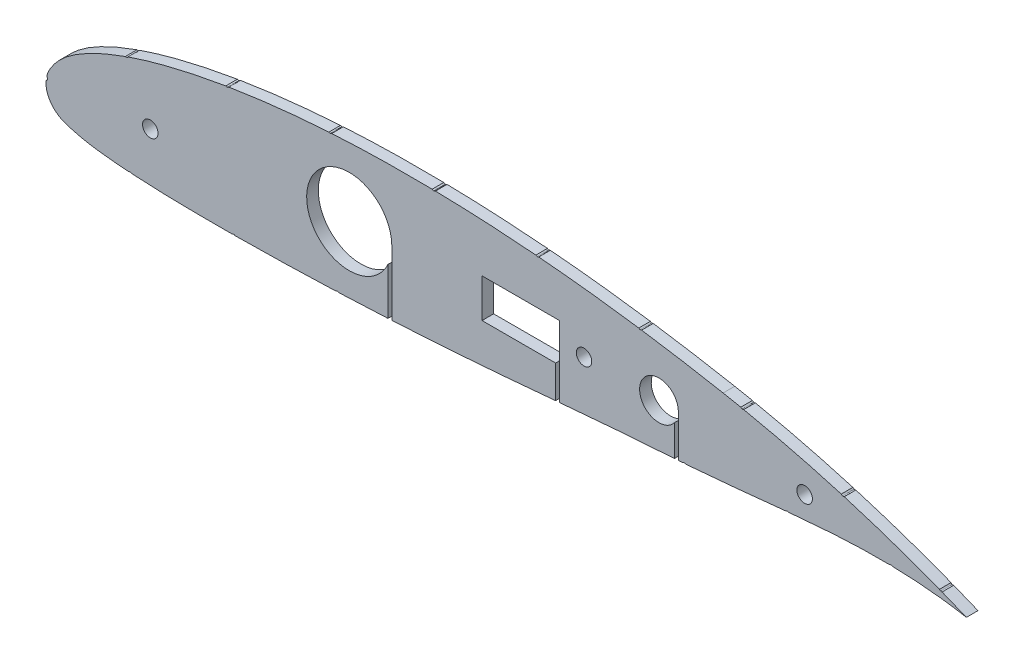
SolidWorks part; units mm, degrees
ref_plane "Front" through (0, 0, 0) normal (0, 0, 1) x (1, 0, 0)
ref_plane "Top" through (0, 0, 0) normal (0, 1, 0) x (1, 0, 0)
ref_plane "Right" through (0, 0, 0) normal (1, 0, 0) x (0, 0, -1)
sketch "Sketch1" plane through (0, 0, 0) normal (0, 0, 1) x (1, 0, 0)
  line L0 (-71.0818, 4.3261) -> (-69.7318, 4.384)
  line L1 (-36.1092, 25.7451) -> (-16.1092, 25.7451)
  line L2 (-36.1092, 25.7451) -> (-36.1092, 15.7451)
  line L3 (-36.1092, 15.7451) -> (-17.1092, 15.7451)
  line L4 (-16.1092, 25.7451) -> (-16.1092, 19.2966)
  line L17 (-50.0108, 5.3795) -> (-47.31, 5.537)
  line L18 (-59.4068, 20.7451) -> (-59.4068, 4.8701)
  line L19 (-60.4068, 16.1625) -> (-60.4068, 4.8198)
  line L20 (-16.1092, 19.2966) -> (-16.1092, 7.7889)
  line L21 (-17.1092, 15.7451) -> (-17.1092, 7.7043)
  line L22 (14.5932, 20.7451) -> (14.5932, 10.502)
  line L23 (13.5932, 17.7451) -> (13.5932, 10.4166)
  circle A0 centre (9.5932, 20.7451) radius 5 construction
  circle A1 centre (-70.4068, 20.7451) radius 11 construction
  arc A2 (14.5932, 20.7451) -> (13.5932, 17.7451) centre (9.5932, 20.7451) ccw
  arc A3 (-59.4068, 20.7451) -> (-60.4068, 16.1625) centre (-70.4068, 20.7451) ccw
  circle A4 centre (-121.8028, 15.7701) radius 2
  circle A5 centre (59.3391, 20.7451) radius 2
  circle A6 centre (-9.7688, 20.7451) radius 2
  spline S0 degree 3 poles (-47.31, 5.537) (-47.1289, 5.5477) (-41.7126, 5.8685) (-31.641, 6.5306) (-21.7599, 7.3125) (-17.1092, 7.7043) knots 0.708178 0.708178 0.708178 0.708178 0.709076 0.735036 0.758139 0.758139 0.758139 0.758139
  spline S1 degree 3 poles (38.2682, 12.331) (41.3825, 12.5361) (49.4822, 13.0301) (62.2579, 13.616) (76.1865, 13.9414) (88.9177, 13.8805) (100.1456, 13.479) (109.7496, 12.7199) (117.0779, 11.8175) (122.9528, 10.7041) (125.3195, 10.2685) (128.1323, 9.5094) (125.6545, 10.4145) (123.8171, 11.2948) (119.5362, 12.9981) (114.2976, 14.7106) (107.4982, 16.6465) (99.4453, 18.7417) (90.1462, 20.9802) (79.7583, 23.308) (68.4053, 25.6742) (56.237, 28.0241) (43.3949, 30.2811) (30.0199, 32.3736) (16.2369, 34.2202) (2.1651, 35.7556) (-12.0689, 36.9617) (-26.3399, 37.814) (-40.517, 38.2756) (-54.4758, 38.3382) (-68.093, 38.0028) (-81.2543, 37.2555) (-93.8487, 36.1153) (-105.7717, 34.6098) (-116.9218, 32.7863) (-127.197, 30.6681) (-136.5081, 28.3232) (-144.7684, 25.7804) (-151.9085, 23.1088) (-157.8744, 20.3632) (-162.6123, 17.6138) (-166.1496, 14.8861) (-168.3325, 12.3394) (-169.3807, 10.5404) (-169.4245, 9.1539) (-168.5264, 7.651) (-165.5653, 6.7783) (-161.3678, 5.642) (-155.4843, 4.8321) (-148.1552, 4.1352) (-139.387, 3.6549) (-129.2981, 3.3595) (-117.9909, 3.2485) (-105.595, 3.3258) (-92.2488, 3.5829) (-80.6385, 3.9408) (-73.4941, 4.2239) (-71.0818, 4.3261) knots 0.852065 0.852065 0.852065 0.852065 0.867514 0.892232 0.915364 0.936485 0.9552 0.971104 0.983751 0.992813 0.998211 1 1.001694 1.006395 1.013462 1.022754 1.034367 1.048191 1.064031 1.081681 1.100894 1.121432 1.143025 1.165434 1.188439 1.211855 1.235496 1.259144 1.282615 1.305702 1.328232 1.35003 1.370944 1.390817 1.409506 1.426857 1.442733 1.457018 1.469615 1.48045 1.489472 1.49673 1.502329 1.506256 1.506442 1.509182 1.513914 1.521178 1.530944 1.543145 1.55767 1.574384 1.59311 1.613638 1.635744 1.659184 1.671136 1.671136 1.671136 1.671136
  spline S2 degree 3 poles (-69.7318, 4.384) (-67.6432, 4.4746) (-64.5347, 4.6167) (-61.4267, 4.7688) (-60.4068, 4.8198) knots 0.673365 0.673365 0.673365 0.673365 0.683714 0.688769 0.688769 0.688769 0.688769
  spline S3 degree 3 poles (-59.4068, 4.8701) (-56.2742, 5.029) (-53.1422, 5.1985) (-50.0108, 5.3795) knots 0.690421 0.690421 0.690421 0.690421 0.705947 0.705947 0.705947 0.705947
  spline S4 degree 3 poles (-16.1092, 7.7889) (-15.7801, 7.8169) (-10.0657, 8.3045) (-0.1675, 9.2094) (9.4042, 10.0578) (13.5932, 10.4166) knots 0.759795 0.759795 0.759795 0.759795 0.76143 0.788184 0.808996 0.808996 0.808996 0.808996
  spline S5 degree 3 poles (14.5932, 10.502) (15.48, 10.5775) (21.719, 11.1047) (29.6096, 11.7304) (36.6179, 12.2199) (38.2682, 12.331) knots 0.810652 0.810652 0.810652 0.810652 0.815057 0.841645 0.849832 0.849832 0.849832 0.849832
  point P24 (-36.1092, 20.7451)
  dimension "D1" = 4
  dimension "D2" = 20
  dimension "D3" = 10
  dimension "D4" = 1
  dimension "D6" = 1
sketch "Sketch5" plane through (0, 0, 0) normal (0, 0, 1) x (1, 0, 0)
  line L0 (-59.4068, 20.7451) -> (-59.4068, 4.1275)
  line L2 (-36.1092, 25.7451) -> (-36.1092, 15.7451) construction
  line L3 (-36.1092, 15.7451) -> (-17.1092, 15.7451) construction
  line L4 (-36.1092, 25.7451) -> (-16.1092, 25.7451) construction
  line L5 (-16.1092, 25.7451) -> (-16.1092, 7.4051)
  line L6 (-36.1092, 25.7451) -> (-36.1092, 15.7451)
  line L7 (-36.1092, 15.7451) -> (-17.1092, 15.7451)
  line L8 (-36.1092, 25.7451) -> (-16.1092, 25.7451)
  line L9 (-17.1092, 15.7451) -> (-17.1092, 7.3158)
  line L10 (-60.4068, 16.1625) -> (-60.4068, 4.0747)
  line L11 (14.5932, 20.7451) -> (14.5932, 9.7879)
  line L12 (13.5932, 17.7451) -> (13.5932, 9.7247)
  circle A1 centre (-121.8028, 15.7701) radius 2 construction
  arc A2 (14.5932, 20.7451) -> (13.5932, 17.7451) centre (9.5932, 20.7451) ccw construction
  circle A3 centre (-9.7688, 20.7451) radius 2 construction
  arc A4 (-59.4068, 20.7451) -> (-60.4068, 16.1625) centre (-70.4068, 20.7451) ccw construction
  circle A5 centre (47.2241, 18.5105) radius 2
  circle A6 centre (-121.8028, 15.7701) radius 2
  arc A7 (14.5932, 20.7451) -> (13.5932, 17.7451) centre (9.5932, 20.7451) ccw
  circle A8 centre (-9.7688, 20.7451) radius 2
  arc A9 (-59.4068, 20.7451) -> (-60.4068, 16.1625) centre (-70.4068, 20.7451) ccw
  spline S0 degree 3 poles (74.5756, 12.9846) (76.6592, 12.4224) (74.8238, 13.0928) (73.4627, 13.7448) (70.2918, 15.0066) (66.4113, 16.2751) (61.3747, 17.7091) (55.4095, 19.2611) (48.5214, 20.9192) (40.8266, 22.6435) (32.417, 24.3963) (23.4035, 26.137) (13.8907, 27.8088) (3.9834, 29.3588) (-6.2263, 30.7267) (-16.6498, 31.864) (-27.1936, 32.7574) (-37.7647, 33.3888) (-48.2662, 33.7307) (-58.606, 33.777) (-68.6928, 33.5286) (-78.442, 32.975) (-87.7711, 32.1304) (-96.603, 31.0153) (-104.8623, 29.6645) (-112.4736, 28.0955) (-119.3707, 26.3585) (-125.4895, 24.4749) (-130.7784, 22.4959) (-135.1976, 20.4622) (-138.7072, 18.4256) (-141.3274, 16.4051) (-142.9444, 14.5186) (-143.7208, 13.1861) (-143.7533, 12.159) (-143.088, 11.0457) (-140.8945, 10.3993) (-137.7853, 9.5576) (-133.4272, 8.9577) (-127.9982, 8.4415) (-121.5032, 8.0857) (-114.03, 7.8669) (-105.6543, 7.7846) (-96.4721, 7.8419) (-86.5861, 8.0324) (-76.1045, 8.3554) (-65.1406, 8.8243) (-53.8056, 9.4267) (-42.2005, 10.1882) (-30.3997, 11.1311) (-18.4747, 12.2197) (-6.5174, 13.2738) (5.3171, 14.2106) (16.842, 14.9588) (27.8634, 15.4643) (38.1808, 15.7053) (47.6113, 15.6602) (55.9283, 15.3628) (63.0424, 14.8005) (68.4707, 14.1321) (72.8225, 13.3073) (74.5756, 12.9846) (76.6592, 12.4224) (74.8238, 13.0928) knots -0.016249 -0.007187 -0.001789 0 0.001694 0.006395 0.013462 0.022754 0.034367 0.048191 0.064031 0.081681 0.100894 0.121432 0.143025 0.165434 0.188439 0.211855 0.235496 0.259144 0.282615 0.305702 0.328232 0.35003 0.370944 0.390817 0.409506 0.426857 0.442733 0.457018 0.469615 0.48045 0.489472 0.49673 0.502329 0.506256 0.506442 0.509182 0.513914 0.521178 0.530944 0.543145 0.55767 0.574384 0.59311 0.613638 0.635744 0.659184 0.683714 0.709076 0.735036 0.76143 0.788184 0.815057 0.841645 0.867514 0.892232 0.915364 0.936485 0.9552 0.971104 0.983751 0.992813 0.998211 1 1.001694 1.006395 1.013462 only from (76.2599, 12.5498) to (76.2599, 12.5498) construction
  spline S1 degree 3 poles (-16.1092, 12.4249) (-12.8979, 12.7106) (-5.7224, 13.3367) (5.3171, 14.2106) (16.842, 14.9588) (27.8634, 15.4643) (38.1808, 15.7053) (47.6113, 15.6602) (55.9283, 15.3628) (63.0424, 14.8005) (68.4707, 14.1321) (72.8225, 13.3073) (74.5756, 12.9846) (76.6592, 12.4224) (74.8238, 13.0928) (73.4627, 13.7448) (70.2918, 15.0066) (66.4113, 16.2751) (61.3747, 17.7091) (55.4095, 19.2611) (48.5214, 20.9192) (40.8266, 22.6435) (32.417, 24.3963) (23.4035, 26.137) (13.8907, 27.8088) (3.9834, 29.3588) (-6.2263, 30.7267) (-16.6498, 31.864) (-27.1936, 32.7574) (-37.7647, 33.3888) (-48.2662, 33.7307) (-58.606, 33.777) (-68.6928, 33.5286) (-78.442, 32.975) (-87.7711, 32.1304) (-96.603, 31.0153) (-104.8623, 29.6645) (-112.4736, 28.0955) (-119.3707, 26.3585) (-125.4895, 24.4749) (-130.7784, 22.4959) (-135.1976, 20.4622) (-138.7072, 18.4256) (-141.3274, 16.4051) (-142.9444, 14.5186) (-143.7208, 13.1861) (-143.7533, 12.159) (-143.088, 11.0457) (-140.8945, 10.3993) (-137.7853, 9.5576) (-133.4272, 8.9577) (-127.9982, 8.4415) (-121.5032, 8.0857) (-114.03, 7.8669) (-105.6543, 7.7846) (-96.4721, 7.8419) (-86.5861, 8.0324) (-76.1045, 8.3554) (-65.1406, 8.8243) (-53.8056, 9.4267) (-42.2005, 10.1882) (-30.3997, 11.1311) (-22.0186, 11.8962) (-17.5701, 12.2946) (-17.1092, 12.3357) knots 0.793512 0.793512 0.793512 0.793512 0.815057 0.841645 0.867514 0.892232 0.915364 0.936485 0.9552 0.971104 0.983751 0.992813 0.998211 1 1.001694 1.006395 1.013462 1.022754 1.034367 1.048191 1.064031 1.081681 1.100894 1.121432 1.143025 1.165434 1.188439 1.211855 1.235496 1.259144 1.282615 1.305702 1.328232 1.35003 1.370944 1.390817 1.409506 1.426857 1.442733 1.457018 1.469615 1.48045 1.489472 1.49673 1.502329 1.506256 1.506442 1.509182 1.513914 1.521178 1.530944 1.543145 1.55767 1.574384 1.59311 1.613638 1.635744 1.659184 1.683714 1.709076 1.735036 1.76143 1.788184 1.791276 1.791276 1.791276 1.791276 construction
  spline S2 degree 3 poles (-59.4068, 4.1275) (-56.0183, 4.3081) (-47.9374, 4.7793) (-35.1604, 5.7012) (-24.5369, 6.6488) (-18.5364, 7.1881) (-17.1925, 7.3083) (-17.1092, 7.3158) knots 1.696188 1.696188 1.696188 1.696188 1.71875 1.75 1.78125 1.78972 1.79028 1.79028 1.79028 1.79028
  spline S3 degree 3 poles (-16.1092, 7.4051) (-16.0258, 7.4125) (-13.0528, 7.6774) (-5.4378, 8.3453) (3.8546, 9.0827) (10.7794, 9.5499) (13.069, 9.6927) (13.5932, 9.7247) knots 0.79252 0.79252 0.79252 0.79252 0.79308 0.8125 0.84375 0.855659 0.859195 0.859195 0.859195 0.859195
  spline S4 degree 3 poles (14.5932, 9.7879) (39.458, 11.4054) (63.9142, 16.5218) (89.0016, 11.9046) knots 0.013226 0.013226 0.013226 0.013226 1 1 1 1
  spline S5 degree 2 poles (23.275, 31.217) (57.3229, 25.0728) (89.0016, 11.9046) knots 0 0 0 1 1 1
  spline S6 degree 3 poles (26.1705, 30.681) (25.0717, 30.8873) (21.6526, 31.5191) (15.9022, 32.5263) (6.579, 34.033) (-5.1331, 35.6661) (-19.2486, 37.1613) (-33.4033, 38.2059) (-47.6089, 38.7589) (-61.832, 38.7789) (-73.7055, 38.3054) (-83.1964, 37.5818) (-90.3084, 36.8561) (-97.4055, 35.9335) (-104.4902, 34.7993) (-111.5574, 33.4138) (-117.418, 32.0272) (-122.0964, 30.7377) (-125.5958, 29.6654) (-129.0783, 28.4751) (-132.5514, 27.136) (-135.4386, 25.8622) (-137.7342, 24.7128) (-139.457, 23.7687) (-141.1834, 22.7096) (-142.6152, 21.7138) (-143.778, 20.7916) (-144.6423, 20.0314) (-145.4885, 19.1918) (-146.2955, 18.2765) (-146.9249, 17.446) (-147.4021, 16.7479) (-147.8615, 15.9873) (-148.2575, 15.1336) (-148.5253, 14.2783) (-148.6524, 13.6789) (-148.7151, 13.1462) (-148.7436, 12.7703) (-148.7363, 12.1171) (-148.6411, 11.3518) (-148.4112, 10.4824) (-147.8996, 9.3327) (-147.1312, 8.2534) (-146.0906, 7.2803) (-145.0342, 6.6043) (-144.0994, 6.1764) (-143.3279, 5.9073) (-142.7444, 5.737) (-142.3247, 5.6181) (-141.7124, 5.4466) (-140.9481, 5.2409) (-139.6795, 4.9232) (-138.0064, 4.5759) (-136.0794, 4.2786) (-134.2325, 4.0482) (-132.4228, 3.849) (-130.0057, 3.6169) (-126.9964, 3.3867) (-123.4041, 3.1871) (-119.8389, 3.041) (-116.2798, 2.9354) (-111.5478, 2.8404) (-105.6422, 2.7932) (-98.5712, 2.8266) (-91.5114, 2.9315) (-84.4586, 3.0969) (-75.0574, 3.391) (-67.0431, 3.7356) (-61.3782, 4.0239) (-60.4068, 4.0747) knots 1.117594 1.117594 1.117594 1.117594 1.125 1.140625 1.15625 1.1875 1.21875 1.25 1.28125 1.3125 1.34375 1.359375 1.375 1.390625 1.40625 1.421875 1.4375 1.445312 1.453125 1.460938 1.46875 1.476562 1.480469 1.484375 1.488281 1.492188 1.494141 1.496094 1.498047 1.5 1.501953 1.50293 1.503906 1.504883 1.505371 1.505859 1.506104 1.506348 1.506592 1.506836 1.507324 1.507812 1.508789 1.509766 1.510742 1.511719 1.512695 1.513672 1.514648 1.515625 1.517578 1.519531 1.523438 1.527344 1.53125 1.535156 1.539062 1.546875 1.554688 1.5625 1.570312 1.578125 1.59375 1.609375 1.625 1.640625 1.65625 1.6875 1.693968 1.693968 1.693968 1.693968
  spline S9 degree 3 poles (38.2682, 12.331) (41.3825, 12.5361) (49.4822, 13.0301) (62.2579, 13.616) (76.1865, 13.9414) (88.9177, 13.8805) (100.1456, 13.479) (109.7496, 12.7199) (117.0779, 11.8175) (122.9528, 10.7041) (125.3195, 10.2685) (128.1323, 9.5094) (125.6545, 10.4145) (123.8171, 11.2948) (119.5362, 12.9981) (114.2976, 14.7106) (107.4982, 16.6465) (99.4453, 18.7417) (90.1462, 20.9802) (79.7583, 23.308) (68.4053, 25.6742) (56.237, 28.0241) (43.3949, 30.2811) (30.0199, 32.3736) (16.2369, 34.2202) (2.1651, 35.7556) (-12.0689, 36.9617) (-26.3399, 37.814) (-40.517, 38.2756) (-54.4758, 38.3382) (-68.093, 38.0028) (-81.2543, 37.2555) (-93.8487, 36.1153) (-105.7717, 34.6098) (-116.9218, 32.7863) (-127.197, 30.6681) (-136.5081, 28.3232) (-144.7684, 25.7804) (-151.9085, 23.1088) (-157.8744, 20.3632) (-162.6123, 17.6138) (-166.1496, 14.8861) (-168.3325, 12.3394) (-169.3807, 10.5404) (-169.4245, 9.1539) (-168.5264, 7.651) (-165.5653, 6.7783) (-161.3678, 5.642) (-155.4843, 4.8321) (-148.1552, 4.1352) (-139.387, 3.6549) (-129.2981, 3.3595) (-117.9909, 3.2485) (-105.595, 3.3258) (-92.2488, 3.5829) (-80.6385, 3.9408) (-73.4941, 4.2239) (-71.0818, 4.3261) knots 0.852065 0.852065 0.852065 0.852065 0.867514 0.892232 0.915364 0.936485 0.9552 0.971104 0.983751 0.992813 0.998211 1 1.001694 1.006395 1.013462 1.022754 1.034367 1.048191 1.064031 1.081681 1.100894 1.121432 1.143025 1.165434 1.188439 1.211855 1.235496 1.259144 1.282615 1.305702 1.328232 1.35003 1.370944 1.390817 1.409506 1.426857 1.442733 1.457018 1.469615 1.48045 1.489472 1.49673 1.502329 1.506256 1.506442 1.509182 1.513914 1.521178 1.530944 1.543145 1.55767 1.574384 1.59311 1.613638 1.635744 1.659184 1.671136 1.671136 1.671136 1.671136 construction
  point P4 (13.5932, 9.7247)
  point P11 (23.275, 31.217)
extrude "Boss-Extrude1" add sketch "Sketch5" along normal blind 3 contours S5 S6 L10 A9 L0 S2 L9 L7 L6 L8 L5 S3 L12 A7 L11 S4 A5 A6 A8
sketch "Sketch6" plane through (0, 0, 3) normal (0, 0, 1) x (1, 0, 0)
  line L0 (-36.1092, 25.7451) -> (-36.1092, 15.7451) construction
  line L1 (-153.7834, -4.2549) -> (96.2166, -4.2549)
  line L2 (-153.7834, -4.2549) -> (-153.7834, 45.7451)
  line L3 (-153.7834, 45.7451) -> (96.2166, 45.7451)
  line L4 (96.2166, -4.2549) -> (96.2166, 45.7451)
  point P4 (-153.7834, 20.7451)
  point P7 (-36.1092, 20.7451)
  dimension "D1" = 50
  dimension "D2" = 250
sketch "Sketch7" plane through (0, 0, 3) normal (0, 0, 1) x (1, 0, 0)
  parabola Q0 (26.17, 30.681) -> (89.0016, 11.9046) focus (18.1472, -130.1817) apex (68.6532, 19.5562) construction
  parabola Q1 (26.17, 30.681) -> (89.0016, 11.9046) focus (18.1472, -130.1817) apex (68.6532, 19.5562) construction
  spline S0 degree 3 poles (-661.8575, 2914.5564) (121.9135, -2960.0191) (-43.0541, 2990.219) (703.5263, -2912.2383) knots -5.708697 -5.708697 -5.708697 -5.708697 6.271096 6.271096 6.271096 6.271096 only from (14.5932, 9.7879) to (89.0016, 11.9046) construction
  spline S1 degree 3 poles (433.8339, 2893.8162) (682.8086, -474.7198) (391.3847, -33.2424) (15.9022, 32.5263) (6.579, 34.033) (-5.1331, 35.6661) (-19.2486, 37.1613) (-33.4033, 38.2059) (-47.6089, 38.7589) (-61.832, 38.7789) (-73.7055, 38.3054) (-83.1964, 37.5818) (-90.3084, 36.8561) (-97.4055, 35.9335) (-104.4902, 34.7993) (-111.5574, 33.4138) (-117.418, 32.0272) (-122.0964, 30.7377) (-125.5958, 29.6654) (-129.0783, 28.4751) (-132.5514, 27.136) (-135.4386, 25.8622) (-137.7342, 24.7128) (-139.457, 23.7687) (-141.1834, 22.7096) (-142.6152, 21.7138) (-143.778, 20.7916) (-144.6423, 20.0314) (-145.4885, 19.1918) (-146.2955, 18.2765) (-146.9249, 17.446) (-147.4021, 16.7479) (-147.8615, 15.9873) (-148.2575, 15.1336) (-148.5253, 14.2783) (-148.6524, 13.6789) (-148.7151, 13.1462) (-148.7436, 12.7703) (-148.7363, 12.1171) (-148.6411, 11.3518) (-148.4112, 10.4824) (-147.8996, 9.3327) (-147.1312, 8.2534) (-146.0906, 7.2803) (-145.0342, 6.6043) (-144.0994, 6.1764) (-143.3279, 5.9073) (-142.7444, 5.737) (-142.3247, 5.6181) (-141.7124, 5.4466) (-140.9481, 5.2409) (-139.6795, 4.9232) (-138.0064, 4.5759) (-136.0794, 4.2786) (-134.2325, 4.0482) (-132.4228, 3.849) (-130.0057, 3.6169) (-126.9964, 3.3867) (-123.4041, 3.1871) (-119.8389, 3.041) (-116.2798, 2.9354) (-111.5478, 2.8404) (-105.6422, 2.7932) (-98.5712, 2.8266) (-91.5114, 2.9315) (-84.4586, 3.0969) (-75.0574, 3.391) (243.6827, 17.0969) (554.4731, 169.7844) (1425.75, 2547.5086) knots -1.367837 -1.367837 -1.367837 -1.367837 1.125 1.140625 1.15625 1.1875 1.21875 1.25 1.28125 1.3125 1.34375 1.359375 1.375 1.390625 1.40625 1.421875 1.4375 1.445312 1.453125 1.460938 1.46875 1.476562 1.480469 1.484375 1.488281 1.492188 1.494141 1.496094 1.498047 1.5 1.501953 1.50293 1.503906 1.504883 1.505371 1.505859 1.506104 1.506348 1.506592 1.506836 1.507324 1.507812 1.508789 1.509766 1.510742 1.511719 1.512695 1.513672 1.514648 1.515625 1.517578 1.519531 1.523438 1.527344 1.53125 1.535156 1.539062 1.546875 1.554688 1.5625 1.570312 1.578125 1.59375 1.609375 1.625 1.640625 1.65625 1.6875 3.762168 3.762168 3.762168 3.762168 only from (26.17, 30.681) to (-60.4068, 4.0747) construction
  spline S2 degree 3 poles (14.5932, 9.7879) (39.458, 11.4054) (63.9142, 16.5218) (89.0016, 11.9046) knots 0.013226 0.013226 0.013226 0.013226 1 1 1 1 construction
  spline S3 degree 3 poles (26.17, 30.681) (25.0714, 30.8873) (21.6524, 31.5191) (15.9022, 32.5263) (6.579, 34.033) (-5.1331, 35.6661) (-19.2486, 37.1613) (-33.4033, 38.2059) (-47.6089, 38.7589) (-61.832, 38.7789) (-73.7055, 38.3054) (-83.1964, 37.5818) (-90.3084, 36.8561) (-97.4055, 35.9335) (-104.4902, 34.7993) (-111.5574, 33.4138) (-117.418, 32.0272) (-122.0964, 30.7377) (-125.5958, 29.6654) (-129.0783, 28.4751) (-132.5514, 27.136) (-135.4386, 25.8622) (-137.7342, 24.7128) (-139.457, 23.7687) (-141.1834, 22.7096) (-142.6152, 21.7138) (-143.778, 20.7916) (-144.6423, 20.0314) (-145.4885, 19.1918) (-146.2955, 18.2765) (-146.9249, 17.446) (-147.4021, 16.7479) (-147.8615, 15.9873) (-148.2575, 15.1336) (-148.5253, 14.2783) (-148.6524, 13.6789) (-148.7151, 13.1462) (-148.7436, 12.7703) (-148.7363, 12.1171) (-148.6411, 11.3518) (-148.4112, 10.4824) (-147.8996, 9.3327) (-147.1312, 8.2534) (-146.0906, 7.2803) (-145.0342, 6.6043) (-144.0994, 6.1764) (-143.3279, 5.9073) (-142.7444, 5.737) (-142.3247, 5.6181) (-141.7124, 5.4466) (-140.9481, 5.2409) (-139.6795, 4.9232) (-138.0064, 4.5759) (-136.0794, 4.2786) (-134.2325, 4.0482) (-132.4228, 3.849) (-130.0057, 3.6169) (-126.9964, 3.3867) (-123.4041, 3.1871) (-119.8389, 3.041) (-116.2798, 2.9354) (-111.5478, 2.8404) (-105.6422, 2.7932) (-98.5712, 2.8266) (-91.5114, 2.9315) (-84.4586, 3.0969) (-75.0574, 3.391) (-67.0431, 3.7356) (-61.3782, 4.0239) (-60.4068, 4.0747) knots 1.117595 1.117595 1.117595 1.117595 1.125 1.140625 1.15625 1.1875 1.21875 1.25 1.28125 1.3125 1.34375 1.359375 1.375 1.390625 1.40625 1.421875 1.4375 1.445312 1.453125 1.460938 1.46875 1.476562 1.480469 1.484375 1.488281 1.492188 1.494141 1.496094 1.498047 1.5 1.501953 1.50293 1.503906 1.504883 1.505371 1.505859 1.506104 1.506348 1.506592 1.506836 1.507324 1.507812 1.508789 1.509766 1.510742 1.511719 1.512695 1.513672 1.514648 1.515625 1.517578 1.519531 1.523438 1.527344 1.53125 1.535156 1.539062 1.546875 1.554688 1.5625 1.570312 1.578125 1.59375 1.609375 1.625 1.640625 1.65625 1.6875 1.693968 1.693968 1.693968 1.693968 construction
  text T0 ". . . . . . . . . . . . . . . . " font "Century Gothic" height in points 28
extrude "Cut-Extrude1" cut sketch "Sketch7" against normal blind 10
